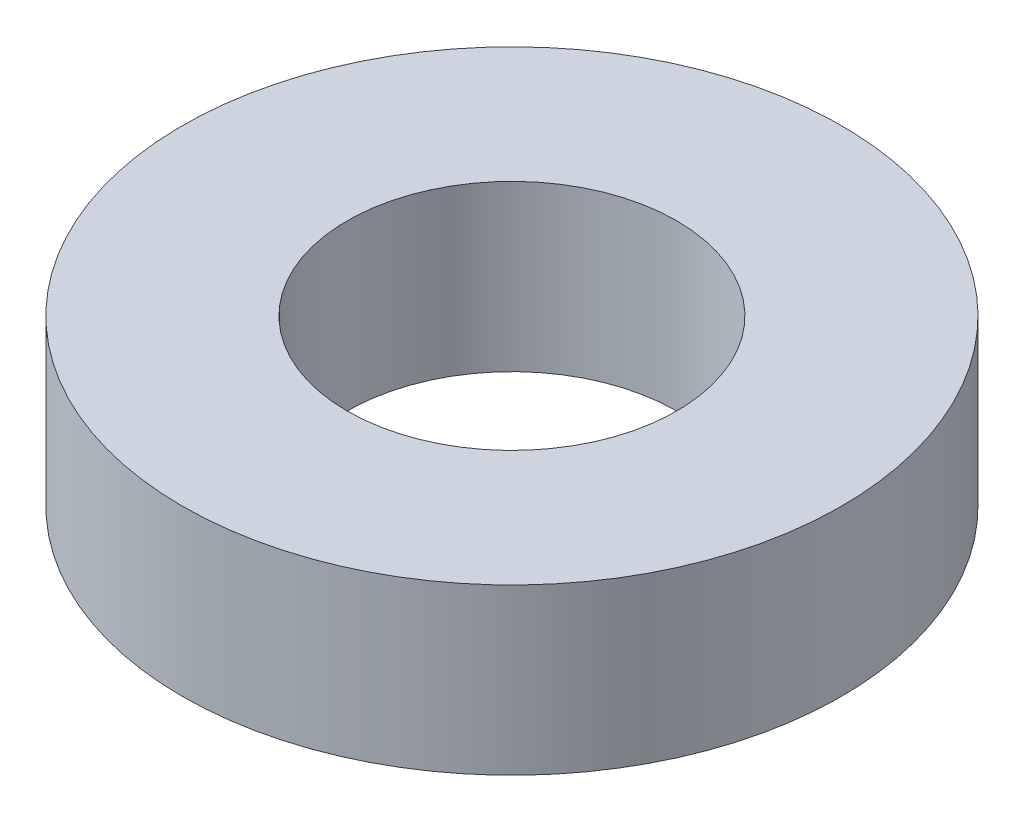
SolidWorks part; units mm, degrees
ref_plane "Front" through (0, 0, 0) normal (0, 0, 1) x (1, 0, 0)
ref_plane "Top" through (0, 0, 0) normal (0, 1, 0) x (1, 0, 0)
ref_plane "Right" through (0, 0, 0) normal (1, 0, 0) x (0, 0, -1)
sketch "Sketch2" plane through (0, 0, 0) normal (0, 1, 0) x (1, 0, 0)
  circle A0 centre (0, 0) radius 1
  circle A1 centre (0, 0) radius 2
  dimension "D1" = 1
  dimension "D2" = 2
extrude "Boss-Extrude1" add sketch "Sketch2" along normal blind 1
